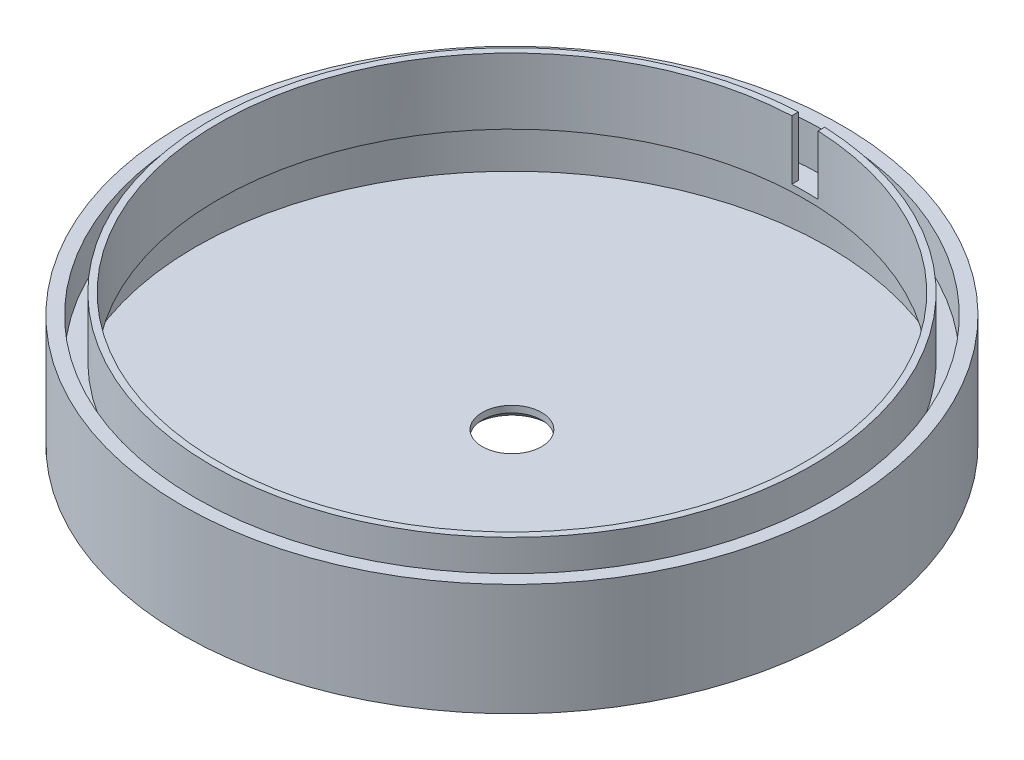
SolidWorks part; units mm, degrees
ref_plane "Plan de face" through (0, 0, 0) normal (0, 0, 1) x (1, 0, 0)
ref_plane "Plan de dessus" through (0, 0, 0) normal (0, 1, 0) x (1, 0, 0)
ref_plane "Plan de droite" through (0, 0, 0) normal (1, 0, 0) x (0, 0, -1)
sketch "Esquisse1" plane through (0, 0, 0) normal (0, 1, 0) x (1, 0, 0)
  circle A0 centre (0, 0) radius 50
  dimension "D1" = 100
extrude "Boss.-Extru.1" add sketch "Esquisse1" along normal blind 17
shell "Coque1" thickness 2
sketch "Esquisse2" plane through (0, 0, 0) normal (0, 1, 0) x (1, 0, 0)
  circle A0 centre (0, 0) radius 4.5
  dimension "D1" = 9
extrude "Enlèv. mat.-Extru.3" cut sketch "Esquisse2" along normal through all
chamfer "Chanfrein1" distance 1 angle 45 1 edges at (0, 0, 4.5)
ref_plane "Plan1" through (0, 10, 0) normal (0, 1, 0) x (1, 0, 0)
sketch "Esquisse3" plane through (0, 10, 0) normal (0, 1, 0) x (1, 0, 0)
  circle A0 centre (0, 0) radius 50
  circle A1 centre (0, 0) radius 44.5
  circle A2 centre (0, 0) radius 50 construction
  dimension "D1" = 5.5
extrude "Boss.-Extru.2" add sketch "Esquisse3" along normal blind 1
sketch "Esquisse4" plane through (0, 10, 0) normal (0, 1, 0) x (1, 0, 0)
  circle A0 centre (0, 0) radius 44.5
  circle A1 centre (0, 0) radius 45.5
  circle A2 centre (0, 0) radius 44.5 construction
  dimension "D1" = 1
extrude "Boss.-Extru.3" add sketch "Esquisse4" along normal blind 10
sketch "Esquisse5" plane through (0, 20, 0) normal (0, 1, 0) x (1, 0, 0)
  line L1 (-2, 46.5) -> (2, 46.5)
  line L2 (-2, 46.5) -> (-2, 44)
  line L3 (-2, 44) -> (2, 44)
  line L4 (2, 46.5) -> (2, 44)
  circle A0 centre (0, 0) radius 45.5 construction
  circle A1 centre (0, 0) radius 44.5 construction
  dimension "D3" = 46.5
  dimension "D1" = 2
  dimension "D2" = 4
  dimension "D4" = 44
extrude "Enlèv. mat.-Extru.4" cut sketch "Esquisse5" against normal up to surface (9 mm away) up to face at (0, 11, 48)
